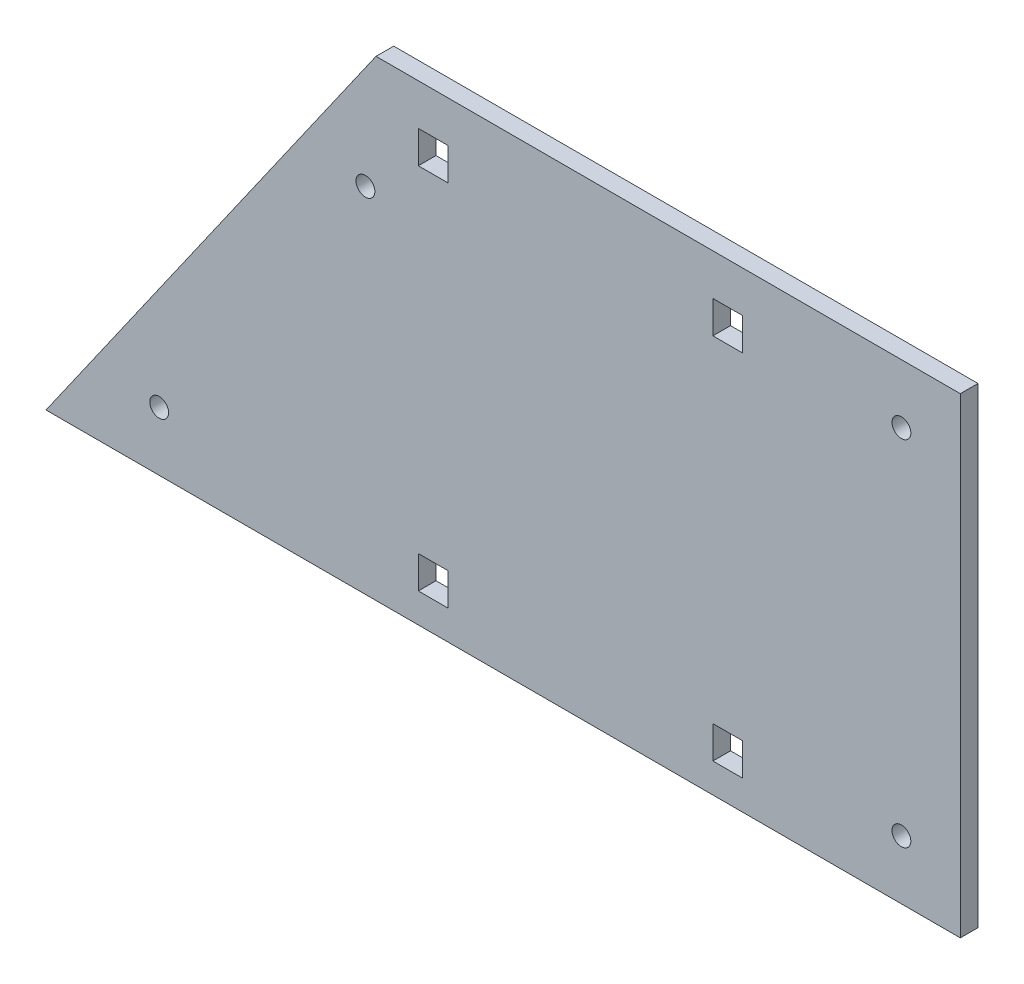
SolidWorks part; units mm, degrees
ref_plane "前视基准面" through (0, 0, 0) normal (0, 0, 1) x (1, 0, 0)
ref_plane "上视基准面" through (0, 0, 0) normal (0, 1, 0) x (1, 0, 0)
ref_plane "右视基准面" through (0, 0, 0) normal (1, 0, 0) x (0, 0, -1)
sketch "草图1" plane through (0, 0, 0) normal (0, 0, 1) x (1, 0, 0)
  line L0 (137.75, -25.25) -> (38.57, -25.25)
  line L1 (38.57, -25.25) -> (-17.4466, -105.25)
  line L2 (-17.4466, -105.25) -> (137.75, -105.25)
  line L3 (137.75, -25.25) -> (137.75, -105.25)
  circle A0 centre (36.7736, -45.25) radius 1.6
  circle A1 centre (1.7632, -95.25) radius 1.6
  circle A2 centre (127.75, -35.25) radius 1.6
  circle A3 centre (127.75, -95.25) radius 1.6
extrude "凸台-拉伸2" add sketch "草图1" along normal blind 3
sketch "草图2" plane through (0, 0, 3) normal (0, 0, 1) x (1, 0, 0)
  line L0 (100.75, -100.25) -> (100.75, -95.4867) construction
  line L1 (100.75, -100.25) -> (95.75, -100.25)
  line L2 (100.75, -100.25) -> (100.75, -94.75)
  line L3 (100.75, -94.75) -> (95.75, -94.75)
  line L4 (95.75, -100.25) -> (95.75, -94.75)
  line L5 (50.75, -100.25) -> (45.75, -100.25)
  line L6 (50.75, -100.25) -> (50.75, -94.75)
  line L7 (50.75, -94.75) -> (45.75, -94.75)
  line L8 (45.75, -100.25) -> (45.75, -94.75)
  line L9 (95.75, -100.25) -> (95.75, -95.4867) construction
  line L10 (95.75, -100.25) -> (88.7275, -100.25) construction
  line L11 (50.75, -95.4867) -> (50.75, -100.25) construction
  line L12 (45.75, -100.25) -> (38.8174, -100.25) construction
  line L13 (45.75, -95.4867) -> (45.75, -100.25) construction
  point P10 (0, 0)
  dimension "D1" = 5.5
  dimension "D2" = 5.5
extrude "切除-拉伸1" cut sketch "草图2" against normal blind 5
pattern_linear "阵列(线性)1" count 2 spacing 62.5 along (0, 1, 0) of "切除-拉伸1"
